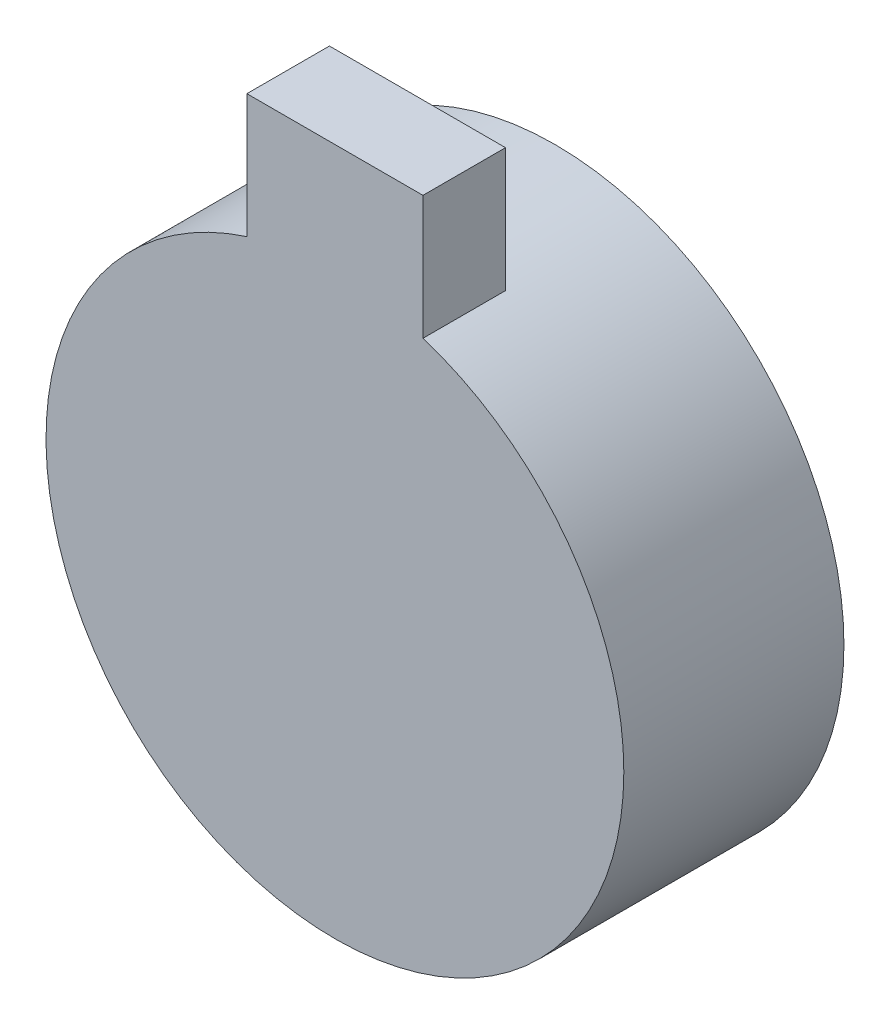
SolidWorks part; units mm, degrees
ref_plane "Ebene vorne" through (0, 0, 0) normal (0, 0, 1) x (1, 0, 0)
ref_plane "Ebene oben" through (0, 0, 0) normal (0, 1, 0) x (1, 0, 0)
ref_plane "Ebene rechts" through (0, 0, 0) normal (1, 0, 0) x (0, 0, -1)
sketch "Skizze1" plane through (0, 0, 0) normal (0, 0, 1) x (1, 0, 0)
  circle A0 centre (-117.144, 15.4564) radius 5.25
  dimension "D1" = 10.5
extrude "Aufsatz-Linear austragen1" add sketch "Skizze1" against normal blind 4
sketch "Skizze2" plane through (0, 0, 0) normal (0, 0, 1) x (1, 0, 0)
  line L0 (-117.144, 15.4564) -> (-117.144, 20.7064) construction
  line L1 (-118.744, 15.4564) -> (-115.544, 15.4564)
  line L2 (-118.744, 15.4564) -> (-118.744, 22.7064)
  line L3 (-118.744, 22.7064) -> (-115.544, 22.7064)
  line L4 (-115.544, 15.4564) -> (-115.544, 22.7064)
  circle A0 centre (-117.144, 15.4564) radius 5.25 construction
  dimension "D1" = 2
  dimension "D2" = 3.2
extrude "Aufsatz-Linear austragen2" add sketch "Skizze2" against normal blind 1.5
